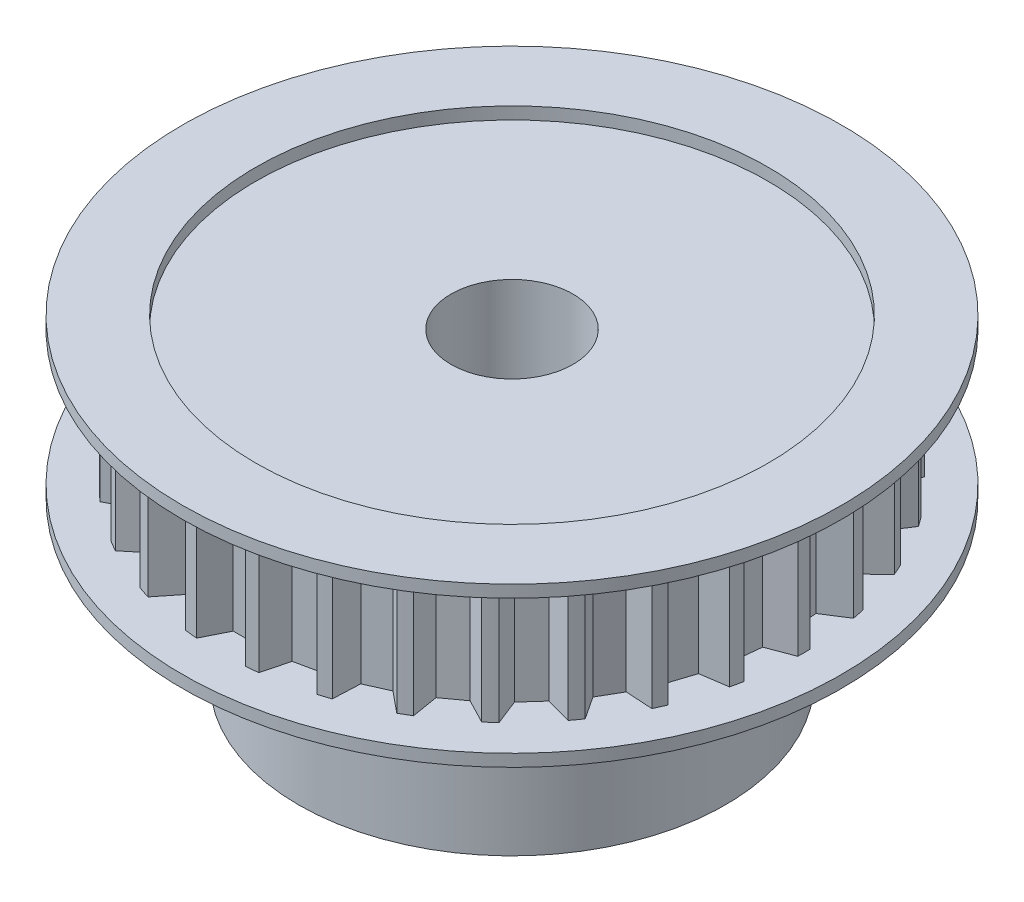
SolidWorks part; units mm, degrees
ref_plane "Front Plane" through (0, 0, 0) normal (0, 0, 1) x (1, 0, 0)
ref_plane "Top Plane" through (0, 0, 0) normal (0, 1, 0) x (1, 0, 0)
ref_plane "Right Plane" through (0, 0, 0) normal (1, 0, 0) x (0, 0, -1)
sketch "Sketch1" plane through (0, 0, 0) normal (0, 1, 0) x (1, 0, 0)
  circle A0 centre (0, 0) radius 23.925
  circle A1 centre (0, 0) radius 5
  dimension "D1" = 47.85
  dimension "D2" = 10
extrude "Boss-Extrude1" add sketch "Sketch1" along normal mid plane 11
sketch "Sketch2" plane through (0, -5.5, 0) normal (0, -1, 0) x (1, 0, 0)
  circle A0 centre (0, 0) radius 4
  circle A1 centre (0, 0) radius 17.5
extrude "Boss-Extrude3" add sketch "Sketch2" along normal blind 14
sketch "Sketch3" plane through (0, 5.5, 0) normal (0, 1, 0) x (1, 0, 0)
  line L0 (0, 0) -> (0, 2) construction
  line L5 (0, 2) -> (0, 23.925) construction
  line L6 (-1, 21.8413) -> (1, 21.8413)
  line L7 (1, 21.8413) -> (2, 23.8413)
  line L9 (-2, 23.8413) -> (-1, 21.8413)
  line L10 (-2, 23.8413) -> (-2.0623, 23.9659)
  line L11 (-2.0623, 23.9659) -> (2.0942, 23.9659)
  line L12 (2.0942, 23.9659) -> (2, 23.8413)
  circle A0 centre (0, 0) radius 23.925 construction
  dimension "D2" = 4
  dimension "D3" = 1
  dimension "D4" = 1
extrude "Cut-Extrude1" cut sketch "Sketch3" against normal up to surface (11 mm away) up to face at (0, -5.5, -17.5)
pattern_circular "CirPattern10" count 30 over 360 about axis through (0, 0, 0) along (0, 1, 0) of "Cut-Extrude1"
sketch "Sketch4" plane through (0, 5.5, 0) normal (0, 1, 0) x (1, 0, 0)
  circle A0 centre (0, 0) radius 27
  circle A1 centre (0, 0) radius 21
  dimension "D1" = 54
  dimension "D2" = 42
extrude "Boss-Extrude4" add sketch "Sketch4" along normal blind 1
sketch "Sketch5" plane through (0, -5.5, 0) normal (0, -1, 0) x (1, 0, 0)
  circle A0 centre (0, 0) radius 27
  circle A1 centre (0, 0) radius 21
  dimension "D1" = 54
  dimension "D2" = 42
extrude "Boss-Extrude5" add sketch "Sketch5" along normal blind 1
